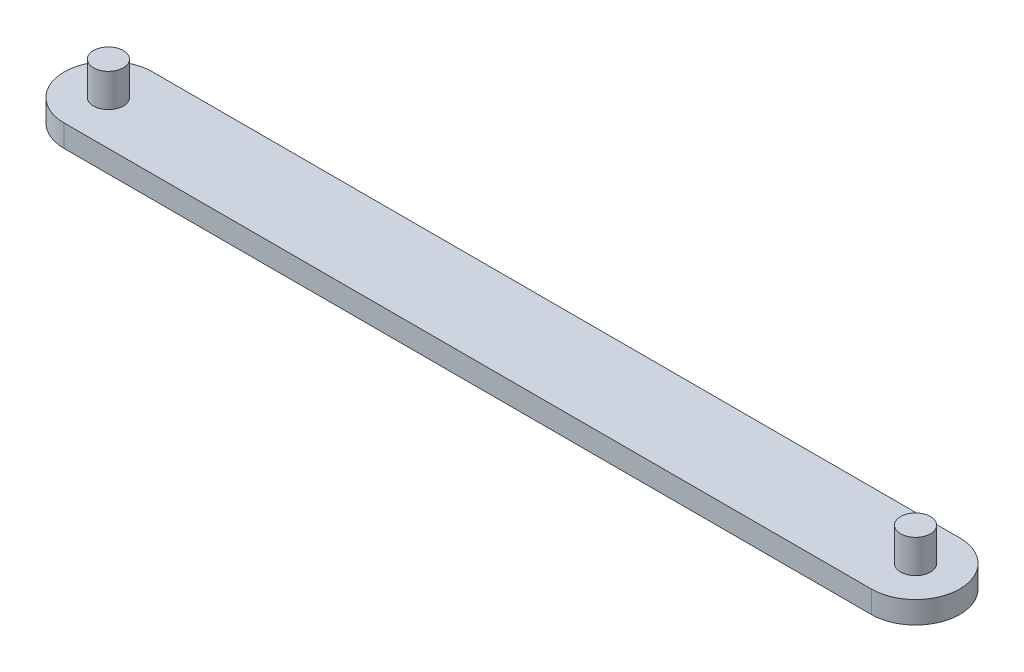
SolidWorks part; units mm, degrees
ref_plane "Front Plane" through (0, 0, 0) normal (0, 0, 1) x (1, 0, 0)
ref_plane "Top Plane" through (0, 0, 0) normal (0, 1, 0) x (1, 0, 0)
ref_plane "Right Plane" through (0, 0, 0) normal (1, 0, 0) x (0, 0, -1)
sketch "Sketch2" plane through (0, 0, 0) normal (0, 1, 0) x (1, 0, 0)
  line L0 (0, -4) -> (0, 4) construction
  line L1 (-36.5, -4) -> (36.5, -4)
  line L3 (-36.5, 4) -> (36.5, 4)
  line L5 (-36.5, -4) -> (36.5, 4) construction
  line L6 (-36.5, 4) -> (36.5, -4) construction
  arc A1 (-36.5, -4) -> (-36.5, 4) centre (-36.5, 0) cw
  arc A2 (36.5, -4) -> (36.5, 4) centre (36.5, 0) ccw
  point P0 (0, 0)
  dimension "D3" = 4
  dimension "D1" = 73
  dimension "D2" = 8
extrude "Boss-Extrude1" add sketch "Sketch2" along normal blind 2
sketch "Sketch3" plane through (0, 2, 0) normal (0, 1, 0) x (1, 0, 0)
  line L0 (0, 4) -> (0, -4) construction
  line L1 (36.5, 4) -> (-36.5, 4) construction
  line L2 (-36.5, -4) -> (36.5, -4) construction
  circle A0 centre (-36.5, 0) radius 1.35
  circle A1 centre (36.5, 0) radius 1.35
  dimension "D1" = 2.7
extrude "Boss-Extrude2" add sketch "Sketch3" along normal blind 3
